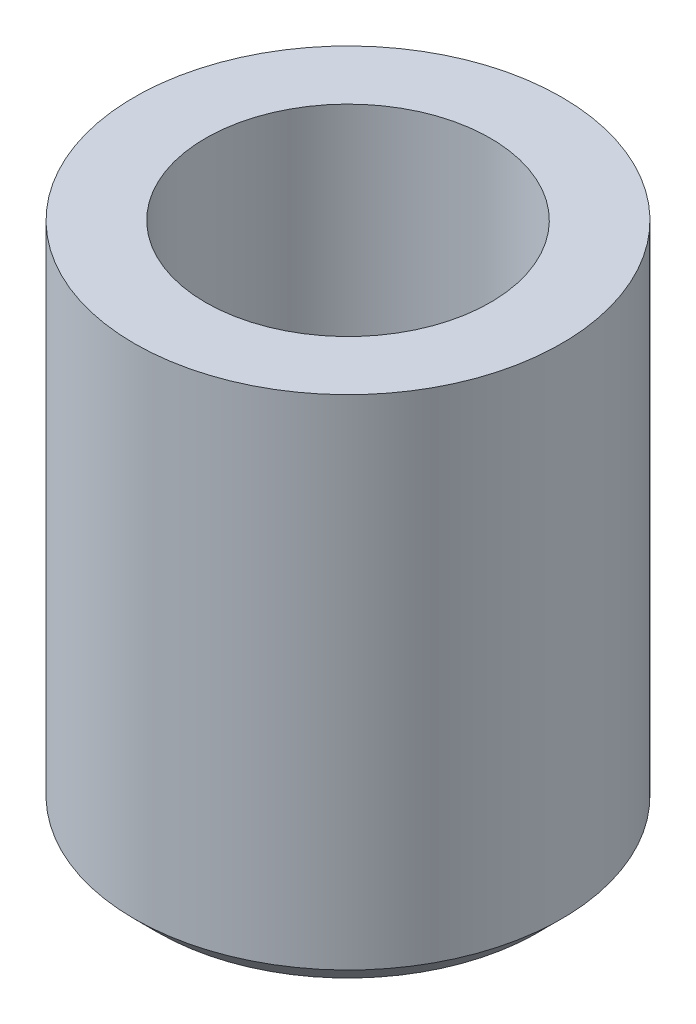
SolidWorks part; units mm, degrees
ref_plane "前视基准面" through (0, 0, 0) normal (0, 0, 1) x (1, 0, 0)
ref_plane "上视基准面" through (0, 0, 0) normal (0, 1, 0) x (1, 0, 0)
ref_plane "右视基准面" through (0, 0, 0) normal (1, 0, 0) x (0, 0, -1)
other "Configuration Table"
sketch "草图1" plane through (0, 0, 0) normal (0, 1, 0) x (1, 0, 0)
  circle A0 centre (0, 0) radius 4.5
  dimension "D1" = 9
extrude "凸台-拉伸1" add sketch "草图1" along normal blind 11
sketch "草图2" plane through (0, 11, 0) normal (0, 1, 0) x (1, 0, 0)
  circle A0 centre (0, 0) radius 3
  dimension "D1" = 6
extrude "切除-拉伸1" cut sketch "草图2" against normal blind 8
chamfer "倒角1" distance 0.5 angle 45 1 edges at (0, 0, 4.5)
